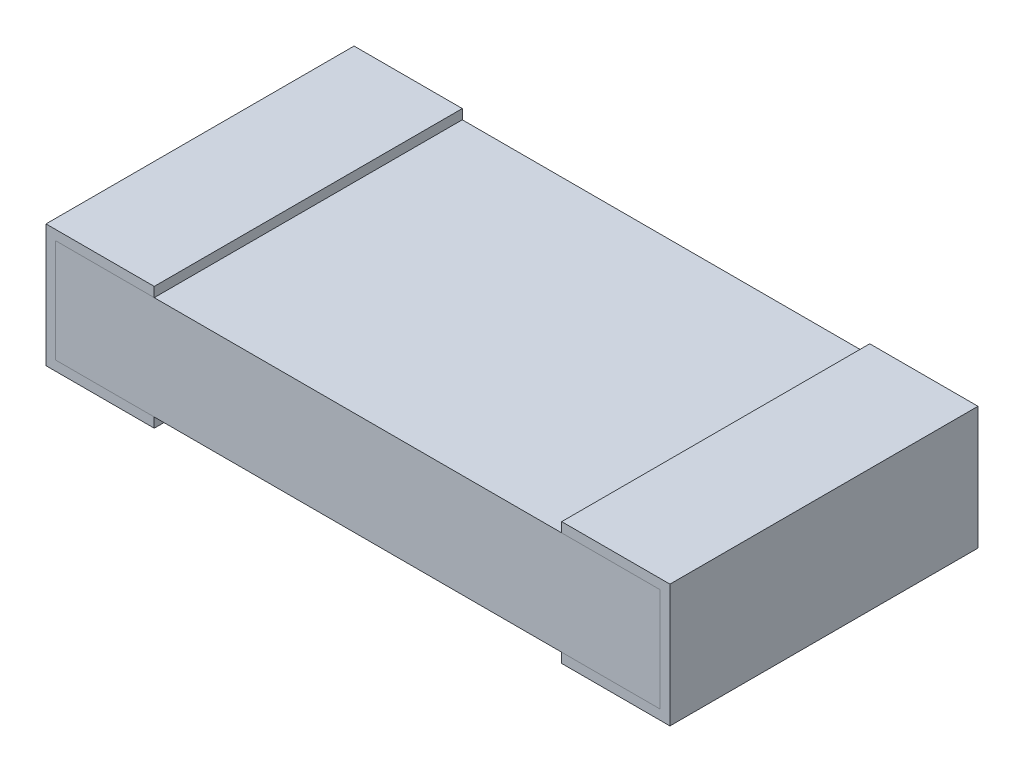
SolidWorks part; units mm, degrees
ref_plane "Front Plane" through (0, 0, 0) normal (0, 0, 1) x (1, 0, 0)
ref_plane "Top Plane" through (0, 0, 0) normal (0, 1, 0) x (1, 0, 0)
ref_plane "Right Plane" through (0, 0, 0) normal (1, 0, 0) x (0, 0, -1)
sketch "Sketch1" plane through (0, 0, 0) normal (0, 0, 1) x (1, 0, 0)
  line L1 (0, 0) -> (3.1, 0)
  line L2 (0, 0) -> (0, 0.53)
  line L3 (0, 0.53) -> (3.1, 0.53)
  line L4 (3.1, 0) -> (3.1, 0.53)
  dimension "D1" = 3.1
  dimension "D2" = 0.53
extrude "Boss-Extrude1" add sketch "Sketch1" along normal blind 1.58
ref_plane "Plane1" through (1.55, 0, 0) normal (-1, 0, 0) x (0, 0, 1)
sketch "Sketch2" plane through (0, 0, 1.58) normal (0, 0, 1) x (1, 0, 0)
  line L1 (3.1, 0.53) -> (0, 0.53) construction
  line L2 (2.5949, 0.53) -> (2.5949, 0.58)
  line L3 (2.5949, 0.58) -> (3.15, 0.58)
  line L4 (3.15, 0.58) -> (3.15, -0.05)
  line L5 (3.15, -0.05) -> (2.5949, -0.05)
  line L6 (2.5949, -0.05) -> (2.5949, 0)
  line L7 (0, 0) -> (3.1, 0) construction
  line L8 (2.5949, 0) -> (3.1, 0)
  line L9 (3.1, 0) -> (3.1, 0.53)
  line L14 (1.55, 0.2915) -> (1.55, -0.2915) construction
  line L16 (0, 0) -> (0, 0.53)
  line L17 (0.5051, 0) -> (0, 0)
  line L18 (0.5051, -0.05) -> (0.5051, 0)
  line L19 (-0.05, -0.05) -> (0.5051, -0.05)
  line L20 (-0.05, 0.58) -> (-0.05, -0.05)
  line L21 (0.5051, 0.58) -> (-0.05, 0.58)
  line L22 (0.5051, 0.53) -> (0.5051, 0.58)
  line L23 (0, 0.53) -> (0.5051, 0.53)
  line L24 (2.5949, 0.53) -> (3.1, 0.53)
  dimension "D1" = 0.05
  dimension "D2" = 0.05
  dimension "D3" = 0.05
extrude "Boss-Extrude2" add sketch "Sketch2" against normal blind 1.58 separate body
